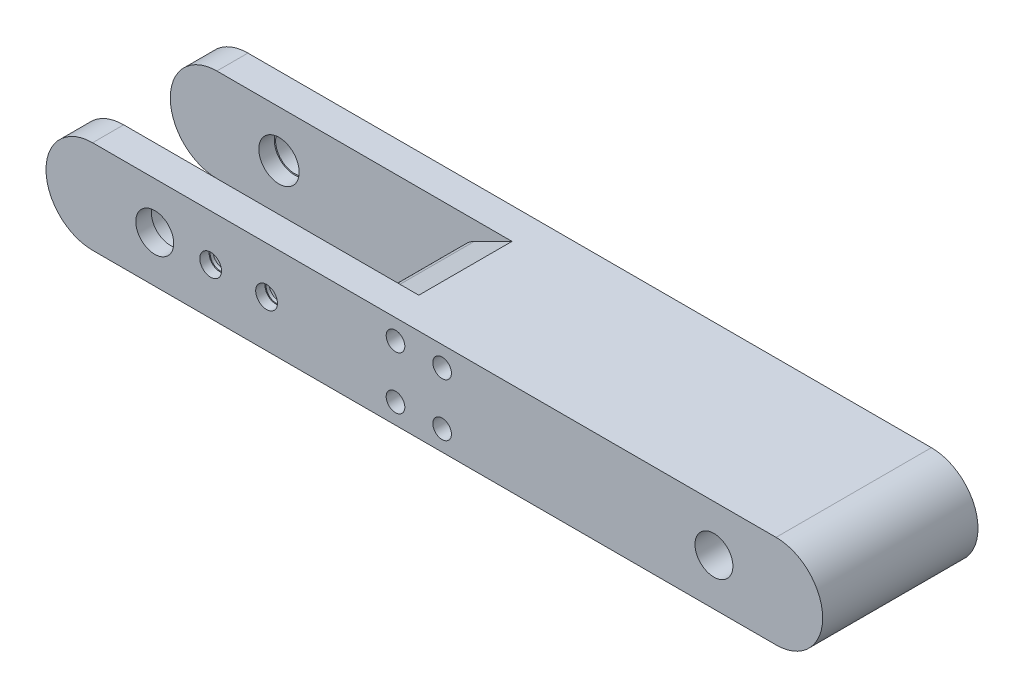
SolidWorks part; units mm, degrees
ref_plane "Front Plane" through (0, 0, 0) normal (0, 0, 1) x (1, 0, 0)
ref_plane "Top Plane" through (0, 0, 0) normal (0, 1, 0) x (1, 0, 0)
ref_plane "Right Plane" through (0, 0, 0) normal (1, 0, 0) x (0, 0, -1)
sketch "Sketch1" plane through (0, 0, 0) normal (0, 0, 1) x (1, 0, 0)
  line L1 (-110, -15) -> (110, -15)
  line L3 (-110, 15) -> (110, 15)
  line L5 (0, 15) -> (0, -15) construction
  line L6 (-113.2069, 0) -> (110, 0) construction
  circle A0 centre (-90, 0) radius 6.1
  circle A1 centre (90, 0) radius 6.1
  arc A2 (-110, -15) -> (-110, 15) centre (-110, 0) cw
  arc A3 (110, -15) -> (110, 15) centre (110, 0) ccw
  point P0 (0, 0)
  dimension "D4" = 12.2
  dimension "D5" = 12.2
  dimension "D1" = 180
  dimension "D2" = 90
  dimension "D3" = 30
  dimension "D6" = 20
  dimension "D7" = 20
extrude "Boss-Extrude1" add sketch "Sketch1" along normal mid plane 50
sketch "Sketch2" plane through (0, 15, 0) normal (0, 1, 0) x (1, 0, 0)
  line L0 (-125, 25) -> (-125, -25) construction
  line L1 (-205, -15) -> (-45, -15)
  line L2 (-205, -15) -> (-205, 15)
  line L3 (-205, 15) -> (-45, 15)
  line L4 (-45, -15) -> (-45, 15)
  line L5 (-125, 15) -> (-125, -15) construction
  line L6 (-205, 0) -> (-45, 0) construction
  point P0 (-125, 0)
  dimension "D1" = 80
  dimension "D2" = 30
extrude "Cut-Extrude1" cut sketch "Sketch2" against normal blind 50
sketch "Sketch4" plane through (0, 0, 15) normal (0, 0, 1) x (1, 0, 0)
  line L0 (-90, 0) -> (90, 0) construction
  line L12 (-45, 15) -> (-45, 0)
  line L13 (110, 15) -> (-110, 15) construction
  line L17 (-45, 0) -> (-15, 15)
  line L18 (-45, 15) -> (-15, 15)
  arc A1 (-110, 15) -> (-110, -15) centre (-110, 0) ccw construction
  point P12 (-125, 0)
  dimension "D1" = 80
  dimension "D2" = 30
extrude "Cut-Extrude5" cut sketch "Sketch4" against normal blind 30
sketch "Sketch7" plane through (0, 0, 15) normal (0, 0, -1) x (-1, 0, 0)
  line L0 (90, 0) -> (-90, 0) construction
  line L1 (45, 0) -> (45, -15)
  line L2 (45, -15) -> (15, -15)
  line L3 (15, -15) -> (45, 0)
  line L4 (110, -15) -> (-110, -15) construction
  arc A0 (110, -15) -> (110, 15) centre (110, 0) ccw construction
  point P10 (125, 0)
  dimension "D1" = 80
  dimension "D2" = 30
extrude "Cut-Extrude7" cut sketch "Sketch7" along normal blind 30
fillet "Fillet3" radius 10 1 edges at (-45, 0, 0)
sketch "Sketch8" plane through (0, 0, 25) normal (0, 0, 1) x (1, 0, 0)
  line L0 (-90, 0) -> (90, 0) construction
  circle A1 centre (-12.5, 8.5) radius 3
  circle A2 centre (2.5, 8.5) radius 3
  circle A3 centre (2.5, -8.5) radius 3
  circle A4 centre (-12.5, -8.5) radius 3
  dimension "D2" = 6
  dimension "D3" = 6
  dimension "D1" = 77.5
  dimension "D4" = 15
  dimension "D5" = 17
  dimension "D6" = 17
extrude "Cut-Extrude8" cut sketch "Sketch8" against normal blind 20
sketch "Sketch9" plane through (0, 0, 25) normal (0, 0, 1) x (1, 0, 0)
  circle A0 centre (-72, 0) radius 3.15
  circle A1 centre (-90, 0) radius 6.1 construction
  circle A2 centre (-54, 0) radius 3.15
  dimension "D1" = 6.3
  dimension "D3" = 6.3
  dimension "D2" = 18
  dimension "D4" = 18
extrude "Cut-Extrude9" cut sketch "Sketch9" against normal blind 4
sketch "Sketch10" plane through (0, 0, 25) normal (0, 0, 1) x (1, 0, 0)
  circle A0 centre (-72, 0) radius 3.5
  circle A1 centre (-54, 0) radius 3.5
  dimension "D1" = 7
  dimension "D2" = 7
extrude "Cut-Extrude10" cut sketch "Sketch10" against normal blind 3
sketch "Sketch11" plane through (0, 0, 15) normal (0, 0, -1) x (-1, 0, 0)
  circle A0 centre (90, 0) radius 6.5
  dimension "D1" = 13
extrude "Cut-Extrude11" cut sketch "Sketch11" against normal blind 5
sketch "Sketch12" plane through (0, 0, -15) normal (0, 0, 1) x (1, 0, 0)
  circle A0 centre (-90, 0) radius 6.5
  dimension "D1" = 13
extrude "Cut-Extrude12" cut sketch "Sketch12" against normal blind 5
equation "\"bearing_d_out\"=12.2"
equation "\"D4@Sketch1\"=\"bearing_d_out\""
equation "\"D5@Sketch1\"=\"bearing_d_out\""
equation "\"thigh_width\"=30"
equation "\"D3@Sketch1\"=\"thigh_width\""
equation "\"thigh_cut_depth\" = 80"
equation "\"D1@Sketch2\"=\"thigh_cut_depth\""
equation "\"D1@Sketch4\"=\"thigh_cut_depth\""
equation "\"cut_depth\" = 30"
equation "\"D2@Sketch4\"=\"cut_depth\""
equation "\"D1@Sketch7\"=\"thigh_cut_depth\""
equation "\"D2@Sketch7\"=\"cut_depth\""
equation "\"cut_width\" = 30"
equation "\"D2@Sketch2\"=\"cut_width\""
equation "\"D1@Cut-Extrude5\"=\"cut_width\""
equation "\"D1@Cut-Extrude7\"=\"cut_width\""
equation "\"link_thickness\" = 50"
equation "\"D1@Boss-Extrude1\"=\"link_thickness\""
